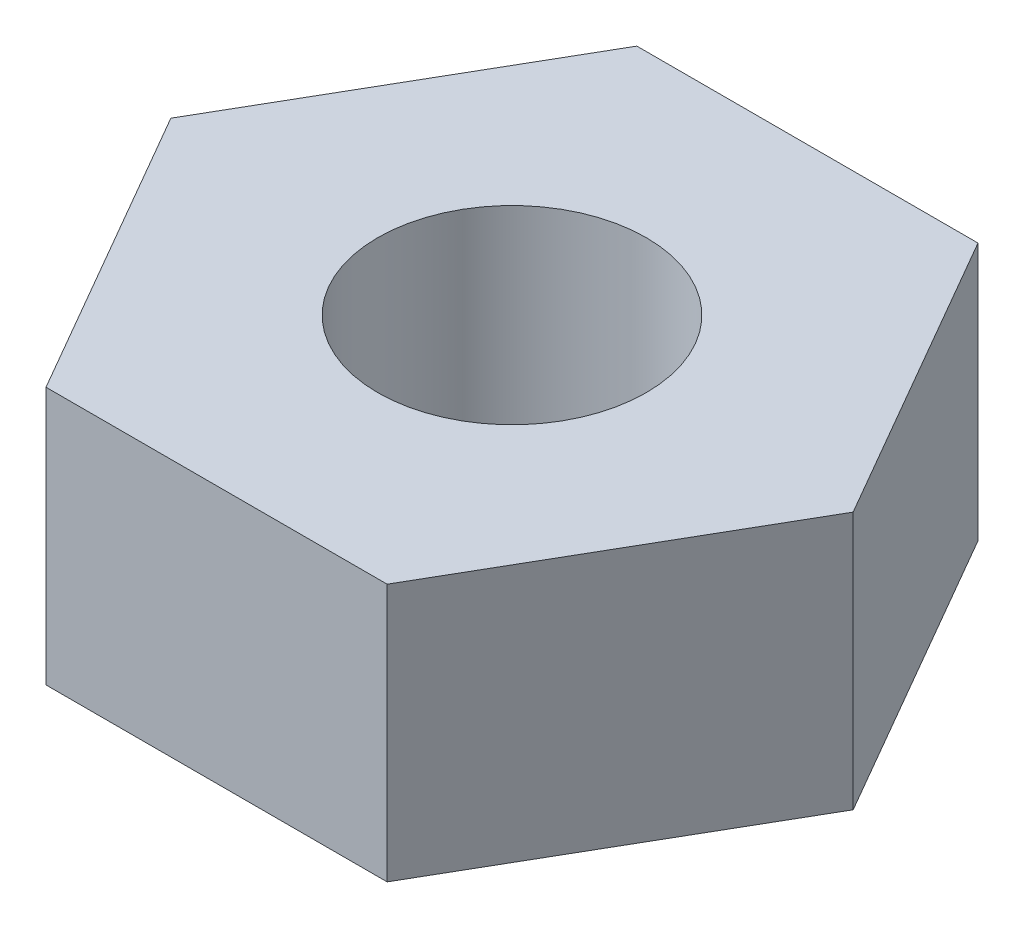
SolidWorks part; units mm, degrees
ref_plane "Спереди" through (0, 0, 0) normal (0, 0, 1) x (1, 0, 0)
ref_plane "Сверху" through (0, 0, 0) normal (0, 1, 0) x (1, 0, 0)
ref_plane "Справа" through (0, 0, 0) normal (1, 0, 0) x (0, 0, -1)
sketch "Эскиз1" plane through (0, 0, 0) normal (0, 1, 0) x (1, 0, 0)
  line L1 (-3.1754, 0) -> (-1.5877, -2.75)
  line L2 (-1.5877, -2.75) -> (1.5877, -2.75)
  line L3 (1.5877, -2.75) -> (3.1754, 0)
  line L4 (3.1754, 0) -> (1.5877, 2.75)
  line L5 (1.5877, 2.75) -> (-1.5877, 2.75)
  line L6 (-1.5877, 2.75) -> (-3.1754, 0)
  circle A0 centre (0, 0) radius 2.75 construction
  dimension "D1" = 5.5
extrude "Бобышка-Вытянуть1" add sketch "Эскиз1" along normal blind 2.4
sketch "Эскиз2" plane through (0, 2.4, 0) normal (0, 1, 0) x (1, 0, 0)
  circle A0 centre (0, 0) radius 1.25
  dimension "D1" = 2.5
extrude "Вырез-Вытянуть1" cut sketch "Эскиз2" against normal blind 2.4
cosmetic thread "Условное изображение резьбы1" parameters "D2"=3
